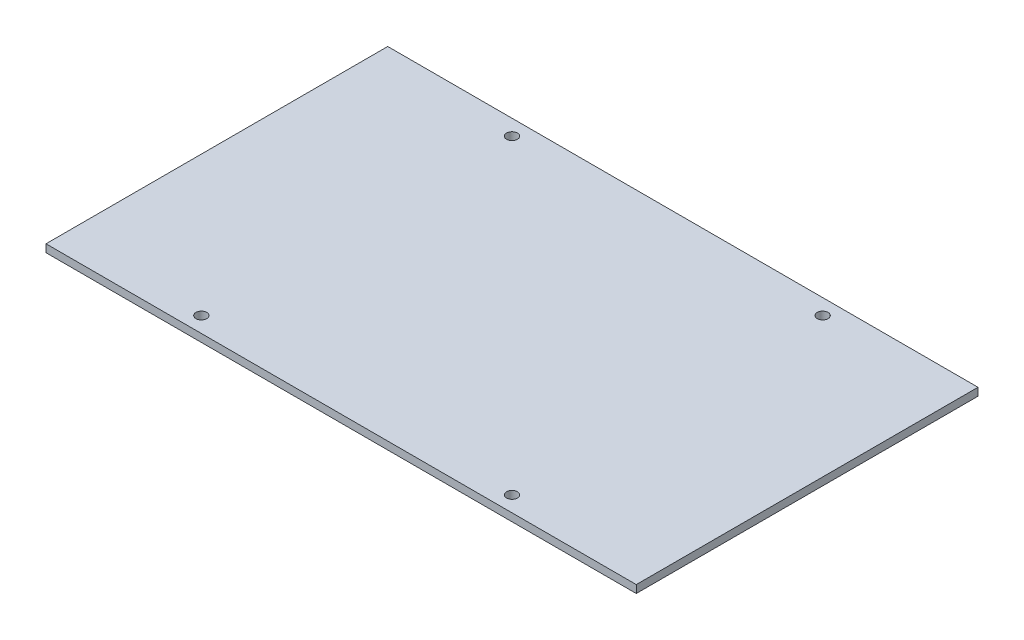
SolidWorks part; units mm, degrees
ref_plane "Front Plane" through (0, 0, 0) normal (0, 0, 1) x (1, 0, 0)
ref_plane "Top Plane" through (0, 0, 0) normal (0, 1, 0) x (1, 0, 0)
ref_plane "Right Plane" through (0, 0, 0) normal (1, 0, 0) x (0, 0, -1)
sketch "Sketch1" plane through (0, 0, 0) normal (0, 1, 0) x (1, 0, 0)
  line L1 (-190, -110) -> (190, -110)
  line L2 (-190, -110) -> (-190, 110)
  line L3 (-190, 110) -> (190, 110)
  line L4 (190, -110) -> (190, 110)
  line L5 (-190, -110) -> (190, 110) construction
  line L6 (-190, 110) -> (190, -110) construction
  point P0 (0, 0)
  dimension "D1" = 220
  dimension "D2" = 380
extrude "Boss-Extrude1" add sketch "Sketch1" along normal mid plane 5
sketch "Sketch4" plane through (0, 2.5, 0) normal (0, 1, 0) x (1, 0, 0)
  line L1 (190, 110) -> (-190, 110) construction
  circle A0 centre (-100, 100) radius 3.5
  dimension "D1" = 7
  dimension "D2" = 100
  dimension "D3" = 10
extrude "Cut-Extrude1" cut sketch "Sketch4" against normal blind 5
mirror "Mirror3" about plane through (0, 0, 0) normal (1, 0, 0) of "Cut-Extrude1"
mirror "Mirror4" about plane through (0, 0, 0) normal (0, 0, 1) of "Mirror3", "Cut-Extrude1"
